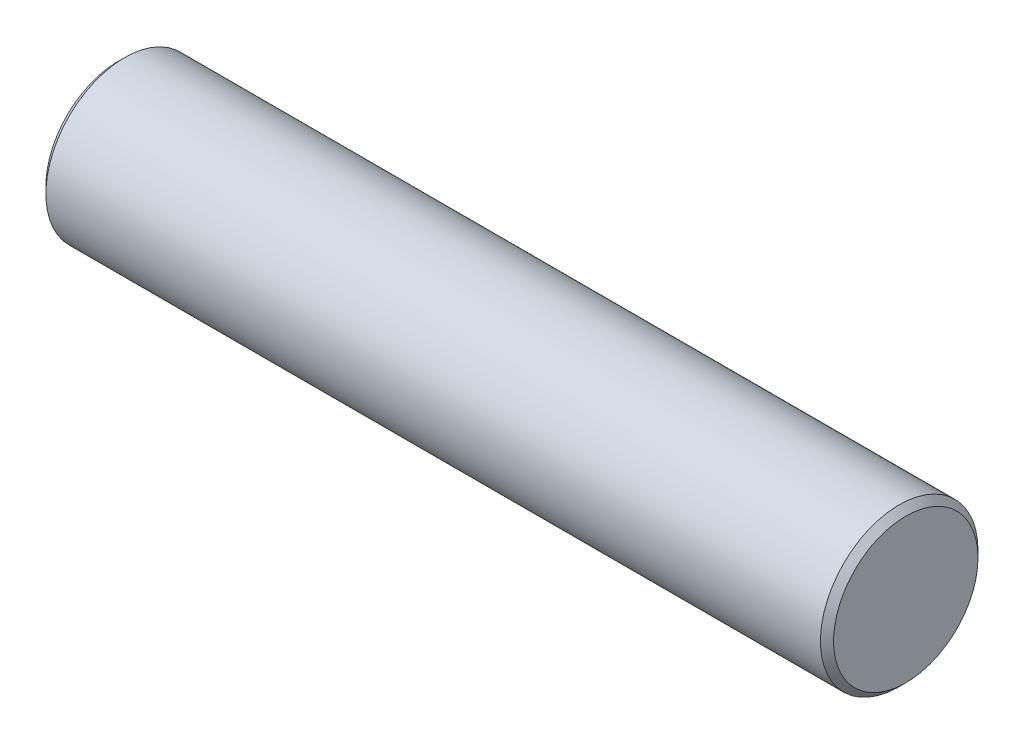
SolidWorks part; units mm, degrees
material "AISI 1045 Steel, cold drawn"
ref_plane "Front Plane" through (0, 0, 0) normal (0, 0, 1) x (1, 0, 0)
ref_plane "Top Plane" through (0, 0, 0) normal (0, 1, 0) x (1, 0, 0)
ref_plane "Right Plane" through (0, 0, 0) normal (1, 0, 0) x (0, 0, -1)
sketch "Sketch1" plane through (0, 0, 0) normal (1, 0, 0) x (0, 0, -1)
  circle A0 centre (0, 0) radius 1.5
  dimension "D1" = 3
extrude "Boss-Extrude1" add sketch "Sketch1" along normal mid plane 15
chamfer "Chamfer1" distance 0.125 angle 45 2 edges at (-7.5, 0, -1.5) (7.5, 0, -1.5)
